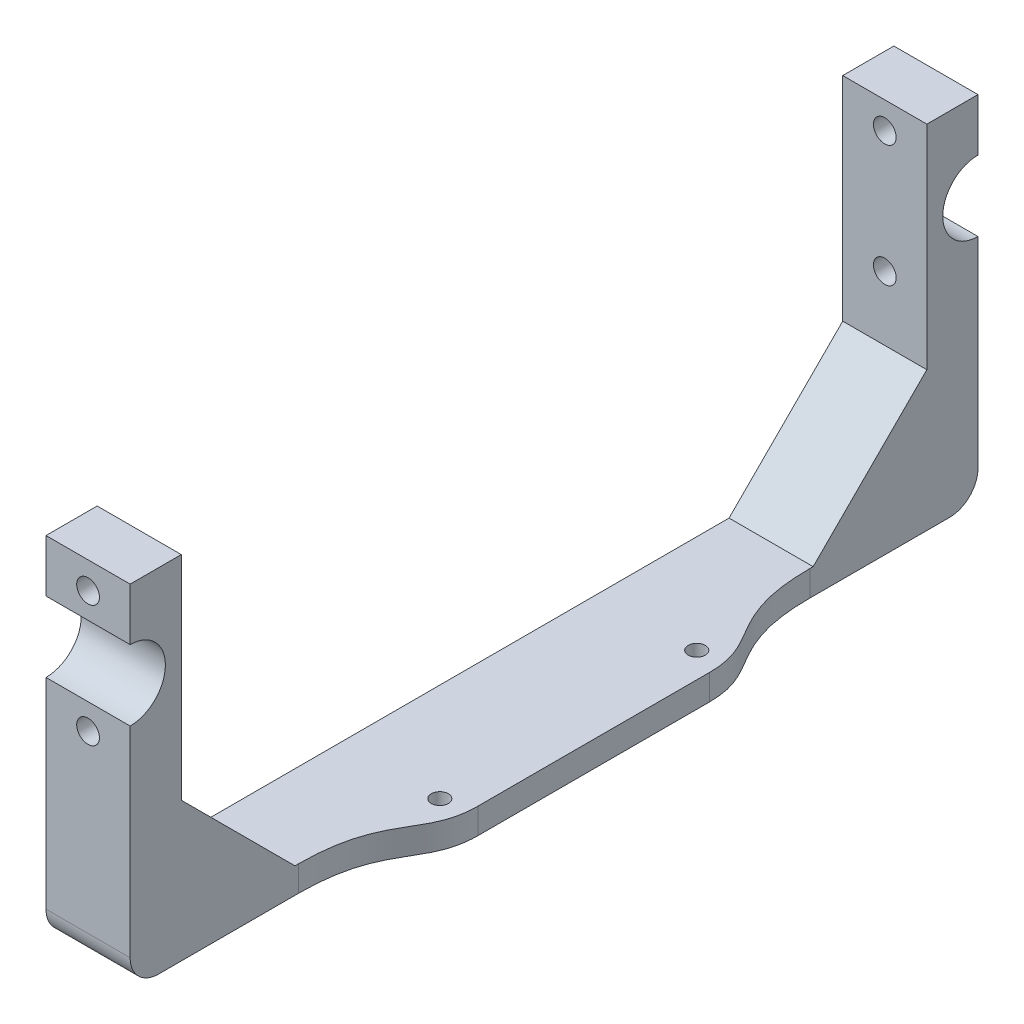
SolidWorks part; units mm, degrees
material "ABS"
ref_plane "Front Plane" through (0, 0, 0) normal (0, 0, 1) x (1, 0, 0)
ref_plane "Top Plane" through (0, 0, 0) normal (0, 1, 0) x (1, 0, 0)
ref_plane "Right Plane" through (0, 0, 0) normal (1, 0, 0) x (0, 0, -1)
sketch "Sketch2" plane through (0, 0, 0) normal (1, 0, 0) x (0, 0, -1)
  line L1 (-90, -4.5) -> (90, -4.5)
  line L2 (-90, -4.5) -> (-90, 4.5)
  line L3 (-90, 4.5) -> (90, 4.5)
  line L4 (90, -4.5) -> (90, 4.5)
  line L5 (-90, -4.5) -> (90, 4.5) construction
  line L6 (-90, 4.5) -> (90, -4.5) construction
  point P0 (0, 0)
  dimension "D1" = 9
  dimension "D2" = 180
extrude "Boss-Extrude1" add sketch "Sketch2" along normal blind 14.8
sketch "Sketch3" plane through (14.8, 0, 0) normal (1, 0, 0) x (0, 0, -1)
  line L0 (-90, -4.5) -> (90, -4.5) construction
  line L1 (-74.579, -4.5) -> (74.579, -4.5) construction
  line L7 (90, -4.5) -> (90, 4.5)
  line L8 (90, 4.5) -> (-90, 4.5)
  line L9 (-90, 4.5) -> (-90, -4.5)
  line L10 (-90, -4.5) -> (90, -4.5)
  line L11 (90, -4.5) -> (90, 4.5)
  line L12 (90, 4.5) -> (-90, 4.5)
  line L13 (-90, 4.5) -> (-90, -4.5)
  arc A0 (-68.379, -4.5) -> (-80.779, -4.5) centre (-74.579, -4.5) ccw
  arc A1 (80.779, -4.5) -> (68.379, -4.5) centre (74.579, -4.5) ccw
  point P10 (0, -4.5)
  dimension "D1" = 6.2
  dimension "D2" = 149.158
  dimension "D4" = 0
extrude "Bar Holes" [suppressed] cut sketch "Sketch3" against normal through all
sketch "Sketch6" [suppressed] plane through (0, 4.5, 0) normal (0, 1, 0) x (1, 0, 0)
  line L0 (7.4, 63.879) -> (7.4, -63.879) construction
  line L1 (14.8, 90) -> (0, 90) construction
  line L2 (14.8, -90) -> (0, -90) construction
  line L3 (0, -68.379) -> (14.8, -68.379) construction
  line L4 (0, -80.779) -> (14.8, -80.779) construction
  line L5 (-32.5661, 0) -> (77.6197, 0) construction
  circle A0 centre (7.4, 63.879) radius 2
  circle A1 centre (7.4, -63.879) radius 2
  circle A2 centre (7.4, -85.279) radius 2
  circle A3 centre (7.4, 85.279) radius 2
  circle A4 centre (7.4, -32.5) radius 3.5 construction
  circle A5 centre (7.4, 32.5) radius 3.5 construction
  circle A6 centre (17.2995, 22.6005) radius 1.5 construction
  circle A8 centre (17.2995, 22.6005) radius 5 construction
  point P4 (7.4, 0)
  point P8 (7.4, 90)
  point P17 (7.4, -90)
  dimension "D1" = 4
  dimension "D2" = 4
  dimension "D5" = 4
  dimension "D6" = 4
  dimension "D10" = 7
  dimension "D11" = 7
  dimension "D7" = 32.5
  dimension "D12" = 3
  dimension "D14" = 9.8995
  dimension "D3" = 4.5
  dimension "D4" = 4.5
  dimension "D8" = 4.5
  dimension "D9" = 32.5
  dimension "D13" = 14
extrude "Bolt Holes" [suppressed] cut sketch "Sketch6" against normal through all
sketch "Sketch7" plane through (14.8, 0, 0) normal (1, 0, 0) x (0, 0, -1)
  line L0 (-90, -4.5) -> (90, -4.5) construction
  line L1 (-90, -4.5) -> (90, -4.5)
  line L2 (-90, -4.5) -> (-90, 0)
  line L3 (-90, 0) -> (90, 0)
  line L4 (90, -4.5) -> (90, 0)
  point P6 (0, 0)
  dimension "D1" = 180
extrude "Cut-Extrude1" cut sketch "Sketch7" against normal through all
sketch "Sketch8" plane through (14.8, 0, 0) normal (1, 0, 0) x (0, 0, -1)
  line L1 (90, 4.5) -> (-90, 4.5) construction
  line L3 (45, 0) -> (45, 4.5)
  line L5 (-45, 0) -> (-45, 4.5)
  line L6 (-45, 4.5) -> (45, 4.5)
  line L7 (45, 0) -> (-45, 0)
extrude "Boss-Extrude2" add sketch "Sketch8" along normal blind 7
sketch "Sketch10" plane through (0, 0, 0) normal (0, -1, 0) x (1, 0, 0)
  line L0 (17.2995, -22.6005) -> (7.4, -32.5) construction
  line L1 (-13.7406, 0) -> (37.2021, 0) construction
  line L4 (14.8, -45) -> (14.8, -29.7858) construction
  line L5 (14.8, -29.7858) -> (21.8, -29.7858) construction
  line L6 (21.8, 45) -> (21.8, -45) construction
  line L7 (21.8, -29.7858) -> (21.8, -20.3664) construction
  line L8 (21.8, -20.3664) -> (30.1723, -20.3664)
  line L9 (30.1723, -20.3664) -> (30.1723, -52.0388)
  line L10 (30.1723, -52.0388) -> (14.8, -52.0388)
  line L12 (14.8, -52.0388) -> (14.8, -45)
  line L13 (30.1723, 52.0388) -> (14.8, 52.0388)
  line L14 (30.1723, 20.3664) -> (30.1723, 52.0388)
  line L15 (21.8, 20.3664) -> (30.1723, 20.3664)
  line L16 (14.8, 45) -> (14.8, 29.7858) construction
  line L17 (14.8, 29.7858) -> (21.8, 29.7858) construction
  line L18 (21.8, 29.7858) -> (21.8, 20.3664) construction
  line L19 (14.8, 52.0388) -> (14.8, 45)
  circle A0 centre (17.2995, -22.6005) radius 1.5
  circle A1 centre (7.4, -32.5) radius 3.5 construction
  circle A2 centre (17.2995, 22.6005) radius 1.5
  spline S0 degree 3 poles (14.8, -45) (14.8, -29.7858) (21.8, -29.7858) (21.8, -20.3664) knots 0 0 0 0 1 1 1 1
  spline S1 degree 3 poles (14.8, 45) (14.8, 29.7858) (21.8, 29.7858) (21.8, 20.3664) knots 0 0 0 0 1 1 1 1
  dimension "D1" = 45
  dimension "D2" = 14
extrude "Cut-Extrude2" cut sketch "Sketch10" against normal blind 8
fillet "Fillet1" [suppressed] radius 8
sketch "Sketch11" plane through (14.8, 0, 0) normal (1, 0, 0) x (0, 0, -1)
  line L0 (74.579, 40.3) -> (74.579, 4.5)
  line L1 (65.579, 46.5) -> (65.579, 4.5)
  line L2 (65.579, 46.5) -> (68.379, 46.5) construction
  line L3 (65.579, 46.5) -> (65.579, 61.92)
  line L4 (90, 4.5) -> (45, 4.5) construction
  line L5 (74.579, 4.5) -> (65.579, 4.5)
  line L6 (74.579, 52.7) -> (74.579, 61.92)
  line L7 (74.579, 61.92) -> (65.579, 61.92)
  line L8 (0, -12.2992) -> (0, 49.2749) construction
  line L9 (-74.579, 52.7) -> (-74.579, 61.92)
  line L10 (-74.579, 61.92) -> (-65.579, 61.92)
  line L11 (-65.579, 46.5) -> (-65.579, 61.92)
  line L12 (-65.579, 46.5) -> (-65.579, 4.5)
  line L13 (-74.579, 4.5) -> (-65.579, 4.5)
  line L14 (-74.579, 40.3) -> (-74.579, 4.5)
  arc A0 (74.579, 52.7) -> (74.579, 40.3) centre (74.579, 46.5) ccw
  arc A2 (-74.579, 52.7) -> (-74.579, 40.3) centre (-74.579, 46.5) cw
  dimension "D1" = 9
  dimension "D2" = 42
  dimension "D3" = 15.42
extrude "Boss-Extrude3" add sketch "Sketch11" against normal blind 14.8
sketch "Sketch12" plane through (0, 0, 74.579) normal (0, 0, 1) x (1, 0, 0)
  line L0 (7.4, 61.92) -> (7.4, 52.7) construction
  line L1 (0, 61.92) -> (14.8, 61.92) construction
  line L2 (0, 52.7) -> (14.8, 52.7) construction
  line L3 (7.4, 52.7) -> (7.4, 40.3) construction
  line L4 (0, 40.3) -> (14.8, 40.3) construction
  line L5 (7.4, 46.5) -> (-1.8066, 46.5) construction
  circle A0 centre (7.4, 57.2) radius 2
  circle A1 centre (7.4, 35.8) radius 2
  dimension "D1" = 4.5
extrude "Cut-Extrude3" cut sketch "Sketch12" against normal through all both and the other way through all
sketch "Sketch13" plane through (0, 0, 0) normal (-1, 0, 0) x (0, 0, 1)
  line L0 (74.579, 4.5) -> (74.579, -10.4296)
  line L1 (74.579, -10.4296) -> (100.927, -10.4296)
  line L2 (100.927, -10.4296) -> (100.927, 4.5)
  line L3 (100.927, 4.5) -> (74.579, 4.5)
  line L4 (0, -9.6936) -> (0, 28.4875) construction
  line L5 (-100.927, -10.4296) -> (-100.927, 4.5)
  line L6 (-74.579, -10.4296) -> (-100.927, -10.4296)
  line L7 (-74.579, 4.5) -> (-74.579, -10.4296)
  line L8 (-100.927, 4.5) -> (-74.579, 4.5)
extrude "Cut-Extrude4" cut sketch "Sketch13" against normal through all both
fillet "Fillet2" radius 5 2 edges at (7.4, 0, 74.579) (7.4, 0, -74.579)
chamfer "Chamfer1" distance 20 angle 45 2 edges at (7.4, 4.5, 65.579) (7.4, 4.5, -65.579)
